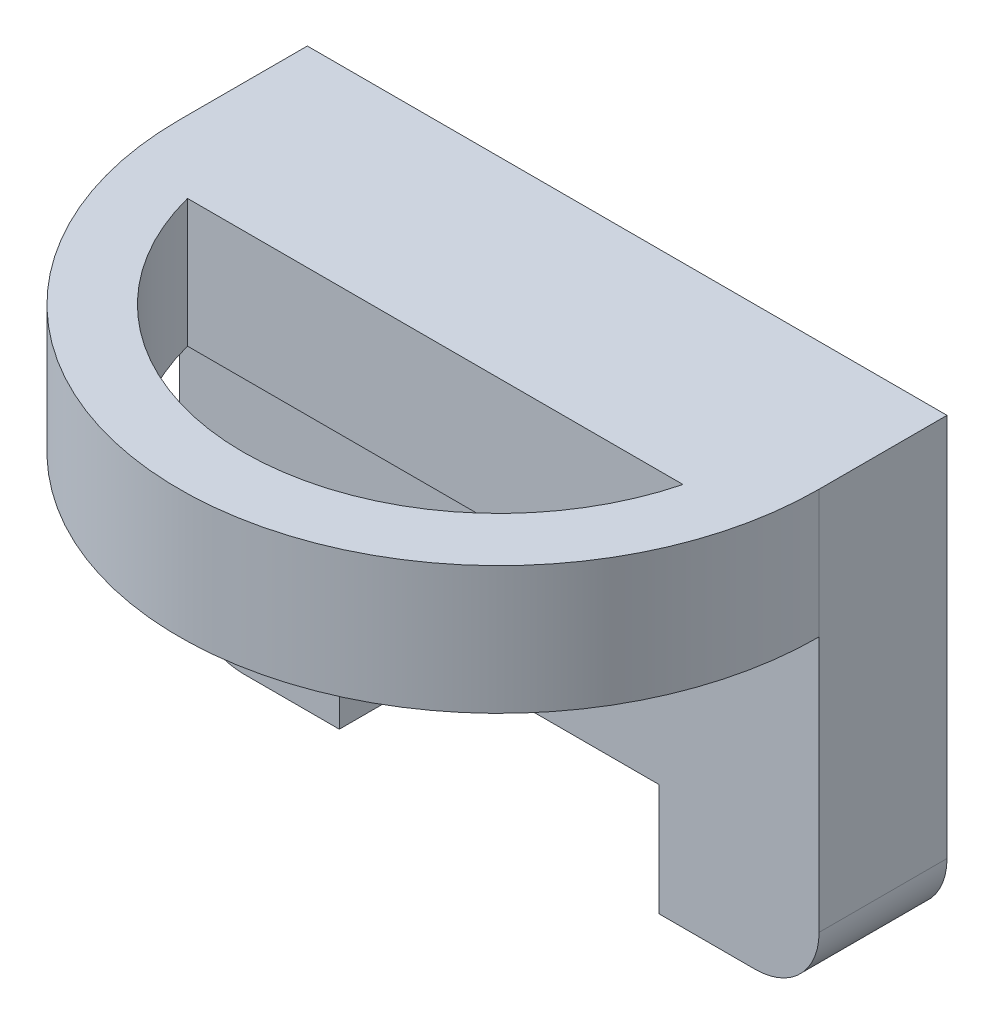
SolidWorks part; units mm, degrees
ref_plane "前基準面" through (0, 0, 0) normal (0, 0, 1) x (1, 0, 0)
ref_plane "上基準面" through (0, 0, 0) normal (0, 1, 0) x (1, 0, 0)
ref_plane "右基準面" through (0, 0, 0) normal (1, 0, 0) x (0, 0, -1)
sketch "草圖1" plane through (0, 0, 0) normal (0, 0, 1) x (1, 0, 0)
  line L0 (25, -35) -> (40, -35)
  line L1 (-50, 35) -> (50, 35)
  line L2 (-50, 35) -> (-50, -25)
  line L3 (-40, -35) -> (-25, -35)
  line L4 (50, 35) -> (50, -25)
  line L5 (-50, 35) -> (50, -35) construction
  line L6 (-50, -35) -> (50, 35) construction
  line L8 (-25, -35) -> (-25, -17.5)
  line L9 (-25, -17.5) -> (25, -17.5)
  line L10 (25, -35) -> (25, -17.5)
  line L11 (-25, -52.5) -> (25, -17.5) construction
  line L12 (-25, -17.5) -> (25, -52.5) construction
  arc A0 (-50, -25) -> (-40, -35) centre (-40, -25) ccw
  arc A1 (40, -35) -> (50, -25) centre (40, -25) ccw
  point P0 (0, 0)
  point P6 (0, -35)
  dimension "D4" = 10
  dimension "D1" = 100
  dimension "D2" = 70
  dimension "D3" = 50
extrude "填料-伸長1" add sketch "草圖1" along normal blind 20
sketch "草圖2" plane through (0, 35, 0) normal (0, 1, 0) x (1, 0, 0)
  line L0 (50, -20) -> (-50, -20) construction
  line L1 (-50, -20) -> (-50, 0) construction
  line L2 (50, -20) -> (-50, -20)
  line L3 (-38.7298, -30) -> (38.7298, -30)
  arc A0 (50, -20) -> (-50, -20) centre (0, -20) cw
  arc A1 (38.7298, -30) -> (-38.7298, -30) centre (0, -20) cw
  point P12 (38.7298, -30)
  point P13 (-38.7298, -30)
  dimension "D2" = 40
  dimension "D1" = 10
extrude "填料-伸長2" add sketch "草圖2" against normal blind 20
